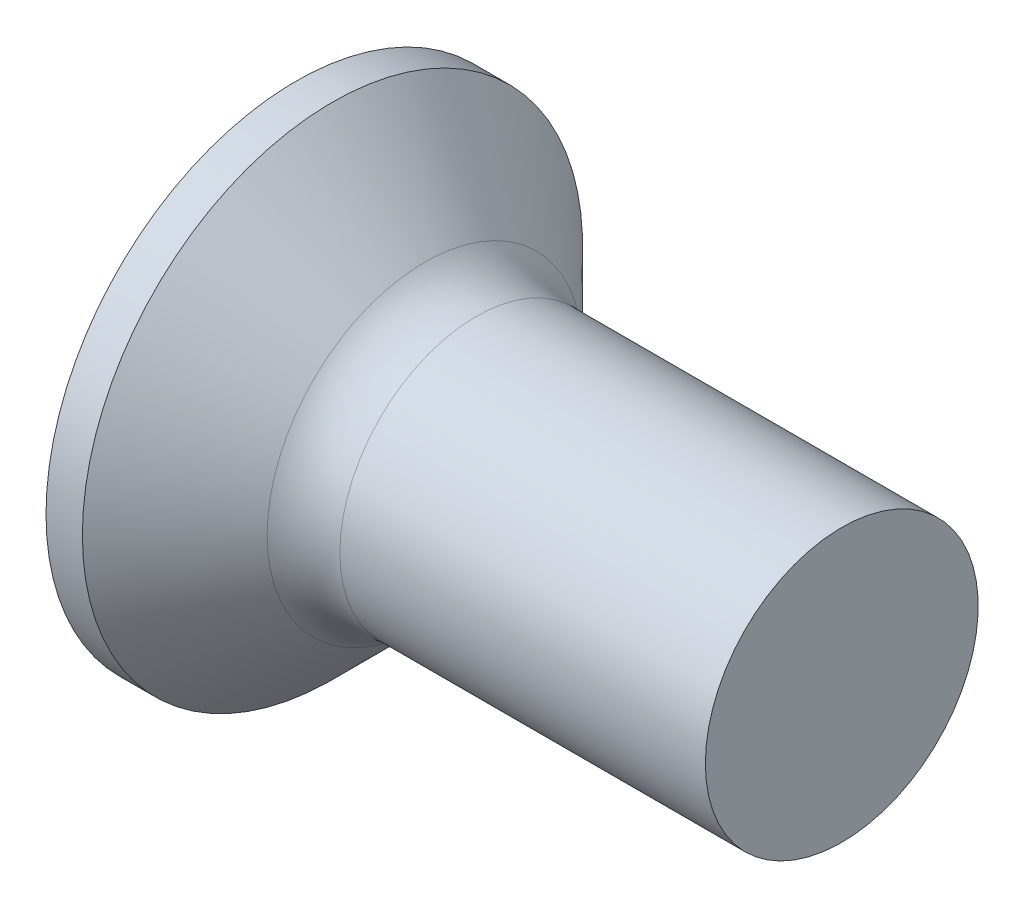
SolidWorks part; units mm, degrees
ref_plane "Plane1" through (0, 0, 0) normal (0, 0, 1) x (1, 0, 0)
ref_plane "Plane2" through (0, 0, 0) normal (0, 1, 0) x (1, 0, 0)
ref_plane "Plane3" through (0, 0, 0) normal (1, 0, 0) x (0, 0, -1)
sketch "BodySke" plane through (0, 0, 0) normal (0, 0, 1) x (1, 0, 0)
  line L0 (0, 0) -> (6.7, 0)
  line L1 (6.7, 0) -> (6.7, 1.5)
  line L2 (6.7, 1.5) -> (2.35, 1.5)
  line L3 (1.1, -2.75) -> (2.35, -1.5) construction
  line L4 (-15.875, 0) -> (82.55, 0) construction
  line L5 (1.1, 2.75) -> (2.35, 1.5)
  line L6 (2.85, 4.675) -> (2.85, -11.2) construction
  line L7 (0.7, 2.7793) -> (0.7, -13.0957) construction
  line L8 (1.1, 2.75) -> (0.7, 2.75)
  arc A0 (0, 0) -> (0.7, 2.75) centre (5.7518, 0) cw
  dimension "Head_ang" = 90
  dimension "Diameter" = 3
  dimension "Advance" = 0.5
  dimension "Thread_nom" = 6
  dimension "Oval_ht" = 0.7
  dimension "Side_ht" = 1.65
  dimension "Head_dia" = 5.5
  dimension "Length" = 6
revolve "Base-Revolve" add sketch "BodySke" angle 360 about L4
cosmetic thread "ThreadCosmetic" [suppressed] parameters "Thread_length"=3.85, "Thread_minor"=2.439
fillet "Fillet1" radius 0.8 1 edges at (2.35, 0, 1.5)
sketch "Sketch3" plane through (0, 0, 0) normal (1, 0, 0) x (0, 0, -1)
  line L0 (0.37, -1.55) -> (-0.37, -1.55)
  line L1 (0.37, -1.55) -> (0.37, 1.55)
  line L2 (-0.37, 1.55) -> (0.37, 1.55)
  line L3 (-0.37, 1.55) -> (-0.37, -1.55)
  dimension "Cross_width" = 0.74
  dimension "D1" = 0.37
  dimension "Cross_dia" = 3.1
  dimension "D2" = 1.55
ref_plane "Plane4" through (2.08, 0, 0) normal (1, 0, 0) x (0, 0, -1)
sketch "Sketch4" plane through (2.08, 0, 0) normal (1, 0, 0) x (0, 0, -1)
  line L0 (0.37, -0.513) -> (-0.37, -0.513)
  line L1 (0.37, -0.513) -> (0.37, 0.513)
  line L2 (-0.37, 0.513) -> (0.37, 0.513)
  line L3 (-0.37, 0.513) -> (-0.37, -0.513)
  dimension "D1" = 0.74
  dimension "D2" = 1.0259
  dimension "D3" = 0.37
  dimension "D4" = 0.513
loft "Recess" cut profiles "Sketch3", "Sketch4"
pattern_circular "RecPat" count 2 every 90 about axis through (0, 0, 0) along (1, 0, 0) of "Recess"
sketch "RecCorSke" plane through (0, 0, 0) normal (0, 0, 1) x (1, 0, 0)
  line L0 (-3.175, 0) -> (15.875, 0) construction
  line L2 (0, 0) -> (0, 0.7014)
  line L3 (0, 0.7014) -> (2.08, 0.556)
  line L4 (2.08, 0.556) -> (2.2607, 0)
  line L5 (2.2607, 0) -> (0, 0)
  dimension "Diameter" = 1.112
  dimension "Depth" = 2.08
  dimension "Draft_angle" = 4
  dimension "Bottom_angle" = 18
revolve "RecessCore" cut sketch "RecCorSke" angle 360 about L0
sketch "ThdSchSke" plane through (0, 0, 0) normal (0, 0, 1) x (1, 0, 0)
  line L0 (2.85, -1.2195) -> (2.6536, -1.5)
  line L1 (2.85, -1.2195) -> (3.0464, -1.5)
  line L2 (3.0464, -1.5) -> (3.0464, -1.875)
  line L3 (-3.175, 0) -> (5.1513, 0) construction
  line L5 (3.0464, -1.875) -> (2.6536, -1.875)
  line L6 (2.6536, -1.875) -> (2.6536, -1.5)
  dimension "Diameter" = 3
  dimension "SideAngle" = 55
  dimension "VeeAngle" = 70
  dimension "Thread_minor" = 2.439
  dimension "Overcut" = 3.75
  dimension "Start" = 2.85
revolve "ThreadSchematic" [suppressed] cut sketch "ThdSchSke" angle 360 about L3
pattern_linear "ThdSchPat" [suppressed]
equation "\"D1@Sketch3\" = \"Cross_width@Sketch3\" / 2"
equation "\"D2@Sketch3\" = \"Cross_dia@Sketch3\" / 2"
equation "\"Depth@RecCorSke\" = \"Cross_depth@Plane4\""
equation "\"D1@Sketch4\" = \"Cross_width@Sketch3\""
equation "\"D2@Sketch4\" = \"Cross_dia@Sketch3\" - 2.0 * \"Cross_depth@Plane4\" * tan(26.5  * 0.017453292)"
equation "\"D3@Sketch4\" = \"D1@Sketch4\" / 2"
equation "\"D4@Sketch4\" = \"D2@Sketch4\" / 2"
equation "\"Thread_length@ThreadCosmetic\" = ((sgn( (\"Length@BodySke\" - \"Advance@BodySke\" - \"Side_ht@BodySke\" ) - \"Thread_nom@BodySke\" )-1)*( (\"Length@BodySke\" - \"Advance@BodySke\" - \"Side_ht@BodySke\" ) - \"Thread_nom@BodySke\" ))/-2+ \"Thread_nom@BodySke\""
equation "\"Thread_minor@ThdSchSke\" = \"Thread_minor@ThreadCosmetic\""
equation "\"Diameter@ThdSchSke\" = \"Diameter@BodySke\""
equation "\"Overcut@ThdSchSke\" = \"Diameter@BodySke\" * 1.25"
equation "\"Start@ThdSchSke\" = \"Oval_ht@BodySke\" + \"Length@BodySke\" - \"Thread_length@ThreadCosmetic\"  '---Countersunk---"
equation "\"Num_threads@ThdSchPat\" = int( \"Thread_length@ThreadCosmetic\" / \"Advance@BodySke\" + 0.999 )  + 1"
equation "\"Advance@ThdSchPat\" = \"Thread_length@ThreadCosmetic\" /  (\"Num_threads@ThdSchPat\" - 1) 'relax it"
